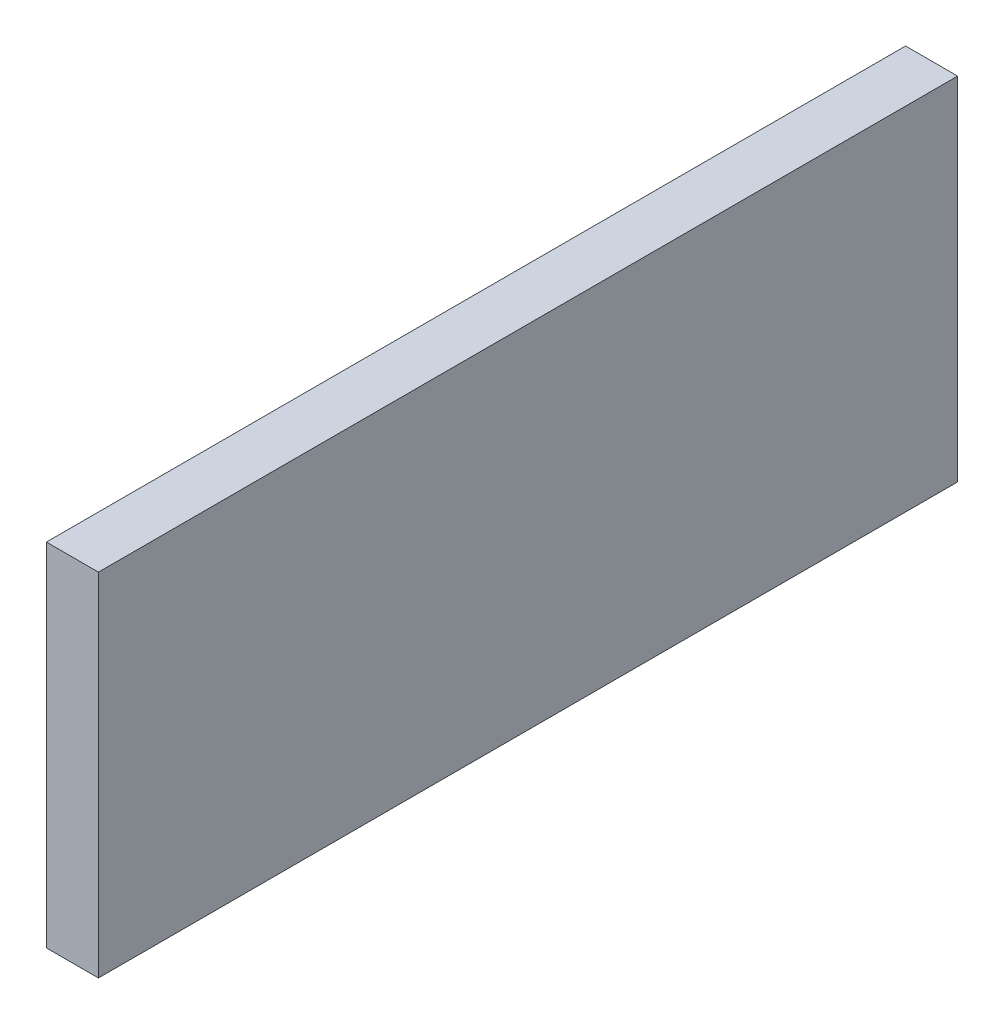
SolidWorks part; units mm, degrees
ref_plane "Спереди" through (0, 0, 0) normal (0, 0, 1) x (1, 0, 0)
ref_plane "Сверху" through (0, 0, 0) normal (0, 1, 0) x (1, 0, 0)
ref_plane "Справа" through (0, 0, 0) normal (1, 0, 0) x (0, 0, -1)
sketch "Эскиз1" plane through (0, 0, 0) normal (0, 0, 1) x (1, 0, 0)
  line L0 (1560, 5540) -> (400, 5540) construction
  line L1 (400, 5540) -> (560, 5540)
  line L2 (400, 5540) -> (400, 6620)
  line L3 (400, 6620) -> (560, 6620)
  line L4 (560, 5540) -> (560, 6620)
  line L5 (400, 5540) -> (400, 6620) construction
  point P6 (400, 6456.5853)
  point P9 (585.6583, 6611.0728)
  point P10 (400, 6620)
  point P12 (559.1164, 6620)
  dimension "D1" = 160
extrude "Бобышка-Вытянуть1" add sketch "Эскиз1" along normal up to surface (2640 mm away)
